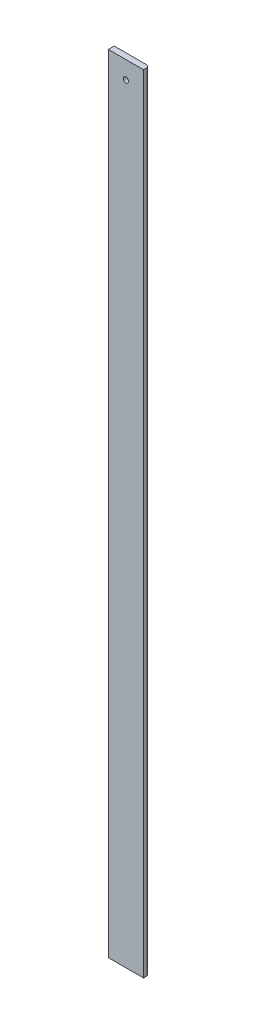
SolidWorks part; units mm, degrees
material "6061 Alloy"
ref_plane "Front Plane" through (0, 0, 0) normal (0, 0, 1) x (1, 0, 0)
ref_plane "Top Plane" through (0, 0, 0) normal (0, 1, 0) x (1, 0, 0)
ref_plane "Right Plane" through (0, 0, 0) normal (1, 0, 0) x (0, 0, -1)
sketch "Sketch2" plane through (0, 0, 0) normal (0, 1, 0) x (1, 0, 0)
  line L0 (0, 0) -> (19.05, 0)
  line L1 (0, 0) -> (0, 19.05)
  line L2 (4.7625, 3.175) -> (17.4625, 3.175)
  line L3 (3.175, 4.7625) -> (3.175, 17.4625)
  line L4 (0, 19.05) -> (1.5875, 19.05)
  line L5 (19.05, 1.5875) -> (19.05, 0)
  line L6 (3.175, 3.175) -> (3.175, 19.05) construction
  line L7 (3.175, 3.175) -> (19.05, 3.175) construction
  arc A0 (3.175, 17.4625) -> (1.5875, 19.05) centre (1.5875, 17.4625) ccw
  arc A1 (3.175, 4.7625) -> (4.7625, 3.175) centre (4.7625, 4.7625) ccw
  arc A2 (17.4625, 3.175) -> (19.05, 1.5875) centre (17.4625, 1.5875) cw
  dimension "D2" = 1.5875
  dimension "D1" = 3.175
extrude "Boss-Extrude1" add sketch "Sketch2" along normal blind 431.8
sketch "Sketch4" plane through (3.175, 0, 0) normal (1, 0, 0) x (0, 0, -1)
  line L0 (19.05, 431.8) -> (19.05, 406.4)
  line L1 (19.05, 431.8) -> (19.05, 0) construction
  line L2 (19.05, 406.4) -> (3.175, 406.4)
  line L3 (3.175, 431.8) -> (3.175, 0) construction
  line L4 (3.175, 406.4) -> (3.175, 431.8)
  line L5 (3.175, 431.8) -> (19.05, 431.8)
extrude "Cut-Extrude1" cut sketch "Sketch4" against normal blind 6.35
sketch "Sketch5" plane through (3.175, 0, 0) normal (-1, 0, 0) x (0, 0, 1)
  line L8 (-4.7625, 406.4) -> (-3.175, 406.4)
  line L9 (-3.175, 406.4) -> (-3.175, 431.8)
  line L10 (-3.175, 431.8) -> (-4.7625, 431.8)
  line L11 (-4.7625, 431.8) -> (-4.7625, 406.4)
  line L12 (-4.7625, 406.4) -> (-3.175, 406.4)
  line L13 (-3.175, 406.4) -> (-3.175, 431.8)
  line L14 (-3.175, 431.8) -> (-4.7625, 431.8)
  line L15 (-4.7625, 431.8) -> (-4.7625, 406.4)
  dimension "D1" = 0
extrude "Cut-Extrude2" cut sketch "Sketch5" against normal blind 6.35
sketch "Sketch6" plane through (3.175, 0, 0) normal (1, 0, 0) x (0, 0, -1)
  line L0 (19.05, 0) -> (3.175, 0) construction
  line L1 (11.1125, 0) -> (11.1125, 15.875) construction
  line L2 (19.05, 406.4) -> (3.175, 406.4) construction
  line L3 (11.1125, 406.4) -> (11.1125, 390.525) construction
  line L4 (11.1125, 15.875) -> (11.1125, 203.2) construction
  line L5 (11.1125, 203.2) -> (11.1125, 390.525) construction
  circle A1 centre (11.1125, 109.5375) radius 1.4224
  circle A2 centre (11.1125, 203.2) radius 1.4224
  circle A3 centre (11.1125, 296.8625) radius 1.4224
  circle A5 centre (11.1125, 11.1125) radius 1.4224
  circle A6 centre (11.1125, 395.2875) radius 1.4224
  point P12 (11.1125, 203.2)
  point P13 (11.1125, 296.8625)
  point P15 (11.1125, 109.5375)
  dimension "D2" = 2.8448
  dimension "D3" = 2.8448
  dimension "D4" = 2.8448
  dimension "D6" = 2.8448
  dimension "D7" = 2.8448
extrude "Cut-Extrude3" cut sketch "Sketch6" against normal blind 5.08
sketch "Sketch7" plane through (0, 431.8, 0) normal (0, 1, 0) x (1, 0, 0)
  line L8 (17.4625, 3.175) -> (0, 3.175)
  line L9 (0, 3.175) -> (0, 0)
  line L10 (0, 0) -> (19.05, 0)
  line L11 (19.05, 0) -> (19.05, 1.5875)
  line L12 (17.4625, 3.175) -> (0, 3.175)
  line L13 (0, 3.175) -> (0, 0)
  line L14 (0, 0) -> (19.05, 0)
  line L15 (19.05, 0) -> (19.05, 1.5875)
  arc A2 (19.05, 1.5875) -> (17.4625, 3.175) centre (17.4625, 1.5875) ccw
  arc A3 (19.05, 1.5875) -> (17.4625, 3.175) centre (17.4625, 1.5875) ccw
  dimension "D1" = 0
extrude "Cut-Extrude4" cut sketch "Sketch7" against normal blind 6.35
sketch "Sketch8" plane through (0, 0, -3.175) normal (0, 0, -1) x (-1, 0, 0)
  line L0 (0, 425.45) -> (0, 415.925) construction
  line L1 (0, 425.45) -> (0, 406.4) construction
  line L2 (0, 415.925) -> (-9.525, 415.925) construction
  circle A0 centre (-9.525, 415.925) radius 1.4224
  dimension "D1" = 2.8448
extrude "Cut-Extrude5" cut sketch "Sketch8" against normal blind 5.08
ref_plane "Plane1" through (0, 0, 2.54) normal (0, 0, 1) x (1, 0, 0)
